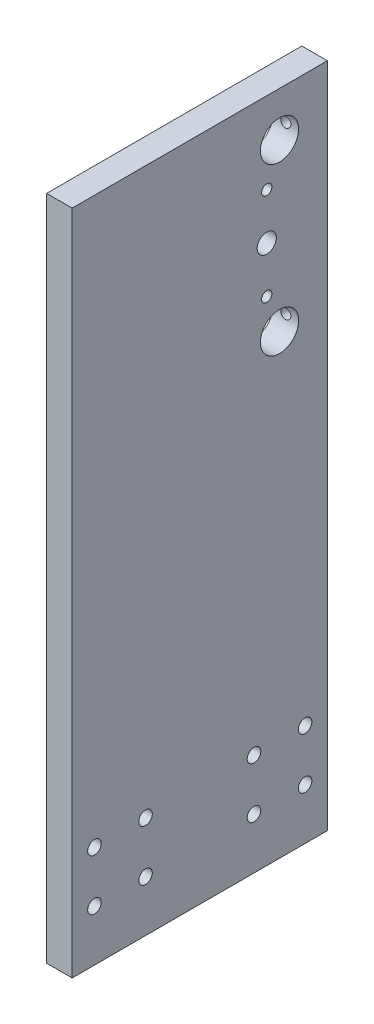
SolidWorks part; units mm, degrees
other "Camera1"
material "6061 Alloy"
ref_plane "Front Plane" through (0, 0, 0) normal (0, 0, 1) x (1, 0, 0)
ref_plane "Top Plane" through (0, 0, 0) normal (0, 1, 0) x (1, 0, 0)
ref_plane "Right Plane" through (0, 0, 0) normal (1, 0, 0) x (0, 0, -1)
sketch "Sketch1" plane through (0, 0, 0) normal (1, 0, 0) x (0, 0, -1)
  line L1 (-63.5, 0) -> (63.5, 0)
  line L2 (-63.5, 0) -> (-63.5, 331.7875)
  line L3 (-63.5, 331.7875) -> (63.5, 331.7875)
  line L4 (63.5, 0) -> (63.5, 331.7875)
  dimension "D1" = 331.7875
  dimension "D2" = 127
extrude "Boss-Extrude1" add sketch "Sketch1" along normal blind 12.7
sketch "Sketch9" plane through (12.7, 0, 0) normal (1, 0, 0) x (0, 0, -1)
  line L0 (63.5, 331.7875) -> (-63.5, 331.7875) construction
  line L1 (63.5, 0) -> (63.5, 331.7875) construction
  line L2 (39.6875, 309.5625) -> (39.6875, 227.0125) construction
  line L3 (39.6875, 268.2875) -> (33.3375, 268.2875) construction
  circle A0 centre (39.6875, 309.5625) radius 9.525
  circle A1 centre (39.6875, 227.0125) radius 9.525
  circle A2 centre (33.3375, 268.2875) radius 4.7625
  dimension "D2" = 19.05
  dimension "D4" = 23.8125
  dimension "D5" = 9.525
  dimension "D6" = 6.35
  dimension "D1" = 22.225
  dimension "D3" = 82.55
extrude "Cut-Extrude1" cut sketch "Sketch9" against normal through all
sketch "Sketch21" [suppressed] plane through (12.7, 0, 0) normal (1, 0, 0) x (0, 0, -1)
  line L1 (23.8125, 296.8625) -> (42.8625, 296.8625)
  line L2 (17.4625, 290.5125) -> (17.4625, 246.0625)
  line L3 (23.8125, 239.7125) -> (42.8625, 239.7125)
  line L4 (49.2125, 290.5125) -> (49.2125, 246.0625)
  line L5 (17.4625, 296.8625) -> (49.2125, 239.7125) construction
  line L6 (17.4625, 239.7125) -> (49.2125, 296.8625) construction
  arc A0 (17.4625, 246.0625) -> (23.8125, 239.7125) centre (23.8125, 246.0625) ccw
  arc A1 (42.8625, 239.7125) -> (49.2125, 246.0625) centre (42.8625, 246.0625) ccw
  arc A2 (42.8625, 296.8625) -> (49.2125, 290.5125) centre (42.8625, 290.5125) cw
  arc A3 (23.8125, 296.8625) -> (17.4625, 290.5125) centre (23.8125, 290.5125) ccw
  point P0 (33.3375, 268.2875)
  dimension "D3" = 6.35
  dimension "D1" = 57.15
  dimension "D2" = 31.75
extrude "Cut-Extrude2" [suppressed] cut sketch "Sketch21" against normal blind 3.175
hole_wizard "#10 Clearance Hole1" [suppressed] positions "Sketch23" profile "Sketch22" hole size "#10" standard "ANSI Inch"
sketch "Sketch23" plane through (9.525, 0, 0) normal (1, 0, 0) x (0, 0, -1)
  line L0 (33.3375, 268.2875) -> (41.6941, 268.2875) construction
  line L2 (41.6941, 287.3375) -> (41.6941, 249.2375) construction
  point P7 (41.6941, 287.3375)
  point P8 (41.6941, 249.2375)
  dimension "D1" = 8.3566
  dimension "D2" = 38.1
sketch "Sketch22" plane through (9.525, 287.3375, -41.6941) normal (0, 1, 0) x (0, 0, -1)
  line L0 (0, 0) -> (0, 9.525)
  line L1 (0, 9.525) -> (2.5527, 9.525)
  line L2 (2.5527, 9.525) -> (2.5527, 0)
  line L5 (2.5527, 0) -> (0, 0)
  line L11 (0, -6.35) -> (0, 107.95) construction
  dimension "Thru Hole Dia." = 5.1054
  dimension "Thru Hole Depth" = 38.1
sketch "Sketch24" plane through (0, 0, 0) normal (-1, 0, 0) x (0, 0, 1)
  line L1 (-42.8625, 296.8625) -> (-23.8125, 296.8625)
  line L2 (-49.2125, 290.5125) -> (-49.2125, 246.0625)
  line L3 (-42.8625, 239.7125) -> (-23.8125, 239.7125)
  line L4 (-17.4625, 290.5125) -> (-17.4625, 246.0625)
  line L5 (-49.2125, 296.8625) -> (-17.4625, 239.7125) construction
  line L6 (-49.2125, 239.7125) -> (-17.4625, 296.8625) construction
  arc A2 (-49.2125, 246.0625) -> (-42.8625, 239.7125) centre (-42.8625, 246.0625) ccw
  arc A3 (-23.8125, 239.7125) -> (-17.4625, 246.0625) centre (-23.8125, 246.0625) ccw
  arc A4 (-23.8125, 296.8625) -> (-17.4625, 290.5125) centre (-23.8125, 290.5125) cw
  arc A5 (-42.8625, 296.8625) -> (-49.2125, 290.5125) centre (-42.8625, 290.5125) ccw
  point P0 (-33.3375, 268.2875)
  dimension "D3" = 6.35
  dimension "D1" = 31.75
  dimension "D2" = 57.15
extrude "Cut-Extrude3" cut sketch "Sketch24" against normal blind 3.175
hole_wizard "#10 Clearance Hole2" positions "Sketch26" profile "Sketch25" hole size "#10" standard "ANSI Inch" end condition up to next
sketch "Sketch26" plane through (3.175, 0, 0) normal (-1, 0, 0) x (0, 0, 1)
  circle A0 centre (-33.3375, 268.2875) radius 23.0124 construction
  point P1 (-33.3375, 291.2999)
  point P2 (-33.3375, 245.2751)
  dimension "D1" = 46.0248
sketch "Sketch25" plane through (3.175, 291.2999, -33.3375) normal (0, 1, 0) x (0, 0, 1)
  line L0 (0, 0) -> (0, 9.525)
  line L1 (0, 9.525) -> (2.5527, 9.525)
  line L2 (2.5527, 9.525) -> (2.5527, 0)
  line L5 (2.5527, 0) -> (0, 0)
  line L11 (0, -6.35) -> (0, 107.95) construction
  dimension "Thru Hole Dia." = 5.1054
  dimension "Thru Hole Depth" = 9.525
hole_wizard "Tapped Hole for #10-32 Helicoil1" positions "Sketch28" profile "Sketch27" tap size "#10-32" standard "Helicoil® Inch"
sketch "Sketch28" plane through (0, 0, -63.5) normal (0, 0, -1) x (-1, 0, 0)
  line L0 (-6.35, 331.7875) -> (-6.35, 225.5554) construction
  line L1 (-12.7, 331.7875) -> (0, 331.7875) construction
  point P6 (-6.35, 325.4375)
  point P8 (-6.35, 211.1375)
  point P12 (-6.35, 309.5625)
  point P14 (-6.35, 227.0125)
  dimension "D1" = 6.35
  dimension "D2" = 114.3
  dimension "D3" = 82.55
  dimension "D4" = 22.225
sketch "Sketch27" plane through (6.35, 325.4375, -63.5) normal (1, 0, 0) x (0, 1, 0)
  line L0 (0, 0) -> (0, 33.2838)
  line L1 (0, 33.2838) -> (2.5527, 31.75)
  line L2 (2.5527, 31.75) -> (2.5527, 0)
  line L5 (2.5527, 0) -> (0, 0)
  line L10 (0, 33.2838) -> (-2.5527, 31.75) construction
  line L11 (0, -6.35) -> (0, 107.95) construction
  dimension "Tap Drill Dia." = 5.1054
  dimension "Tap Drill Depth" = 31.75
  dimension "Drill Angle" = 118
cosmetic thread "Hole Thread13" parameters "D1"=11.43, "D2"=5.936
cosmetic thread "Hole Thread14" parameters "D1"=11.43, "D2"=5.936
cosmetic thread "Hole Thread15" parameters "D1"=11.43, "D2"=5.936
cosmetic thread "Hole Thread16" parameters "D1"=11.43, "D2"=5.936
hole_wizard "1/4 Clearance Hole1" positions "Sketch31" profile "Sketch30" hole size "1/4" standard "ANSI Inch" end condition up to next
sketch "Sketch31" plane through (12.7, 0, 0) normal (1, 0, 0) x (0, 0, -1)
  line L1 (-52.3875, 25.4) -> (-26.9875, 25.4) construction
  line L2 (-52.3875, 25.4) -> (-52.3875, 50.8) construction
  line L3 (-52.3875, 50.8) -> (-26.9875, 50.8) construction
  line L4 (-26.9875, 25.4) -> (-26.9875, 50.8) construction
  line L5 (-52.3875, 50.8) -> (-26.9875, 25.4) construction
  line L8 (26.9875, 50.8) -> (52.3875, 50.8) construction
  line L9 (26.9875, 50.8) -> (26.9875, 25.4) construction
  line L10 (26.9875, 25.4) -> (52.3875, 25.4) construction
  line L11 (52.3875, 50.8) -> (52.3875, 25.4) construction
  line L12 (26.9875, 50.8) -> (52.3875, 25.4) construction
  line L13 (-39.6875, 38.1) -> (-63.5, 38.1) construction
  line L14 (-63.5, 331.7875) -> (-63.5, 0) construction
  line L15 (39.6875, 38.1) -> (63.5, 38.1) construction
  line L16 (63.5, 0) -> (63.5, 331.7875) construction
  line L17 (-63.5, 0) -> (63.5, 0) construction
  point P1 (-52.3875, 25.4)
  point P2 (-26.9875, 50.8)
  point P189 (-52.3875, 50.8)
  point P190 (-26.9875, 25.4)
  point P197 (26.9875, 50.8)
  point P198 (52.3875, 25.4)
  point P287 (26.9875, 25.4)
  point P288 (52.3875, 50.8)
  dimension "D1" = 25.4
  dimension "D2" = 11.1125
  dimension "D3" = 25.4
sketch "Sketch30" plane through (12.7, 25.4, 52.3875) normal (0, 1, 0) x (0, 0, -1)
  line L0 (0, 0) -> (0, 12.7)
  line L1 (0, 12.7) -> (3.3782, 12.7)
  line L2 (3.3782, 12.7) -> (3.3782, 0)
  line L5 (3.3782, 0) -> (0, 0)
  line L11 (0, -6.35) -> (0, 107.95) construction
  dimension "Thru Hole Dia." = 6.7564
  dimension "Thru Hole Depth" = 12.7
hole_wizard " Clearance Hole5" [suppressed] positions "Sketch39" profile "Sketch38" hole size "#4" standard "ANSI Inch"
sketch "Sketch39" plane through (12.7, 0, 0) normal (1, 0, 0) x (0, 0, -1)
  line L0 (-6.35, 177.8) -> (6.35, 177.8) construction
  line L2 (0, 177.8) -> (0, 0) construction
  point P0 (-6.35, 177.8)
  point P1 (6.35, 177.8)
  dimension "D1" = 12.7
  dimension "D2" = 177.8
sketch "Sketch38" plane through (12.7, 177.8, 6.35) normal (0, 1, 0) x (0, 0, -1)
  line L0 (0, 0) -> (0, 12.7)
  line L1 (0, 12.7) -> (2.5527, 12.7)
  line L2 (2.5527, 12.7) -> (2.5527, 0)
  line L5 (2.5527, 0) -> (0, 0)
  line L11 (0, -6.35) -> (0, 107.95) construction
  dimension "Thru Hole Dia." = 3.2639
  dimension "Thru Hole Depth" = 12.7
hole_wizard "#10 Clearance Hole4" [suppressed] positions "Sketch41" profile "Sketch40" hole size "#10" standard "ANSI Inch"
sketch "Sketch41" plane through (0, 0, 0) normal (-1, 0, 0) x (0, 0, 1)
  line L0 (-6.35, 38.1) -> (6.35, 38.1) construction
  line L3 (0, 38.1) -> (0, 0) construction
  point P0 (-6.35, 38.1)
  point P1 (6.35, 38.1)
  dimension "D1" = 38.1
  dimension "D2" = 12.7
sketch "Sketch40" plane through (0, 38.1, -6.35) normal (0, 1, 0) x (0, 0, 1)
  line L0 (0, 0) -> (0, 20.5838)
  line L1 (0, 20.5838) -> (2.5527, 19.05)
  line L2 (2.5527, 19.05) -> (2.5527, 0)
  line L5 (2.5527, 0) -> (0, 0)
  line L10 (0, 20.5838) -> (-2.5527, 19.05) construction
  line L11 (0, -6.35) -> (0, 107.95) construction
  dimension "Hole Dia." = 5.1054
  dimension "Hole Depth" = 19.05
  dimension "Drill Angle" = 118
